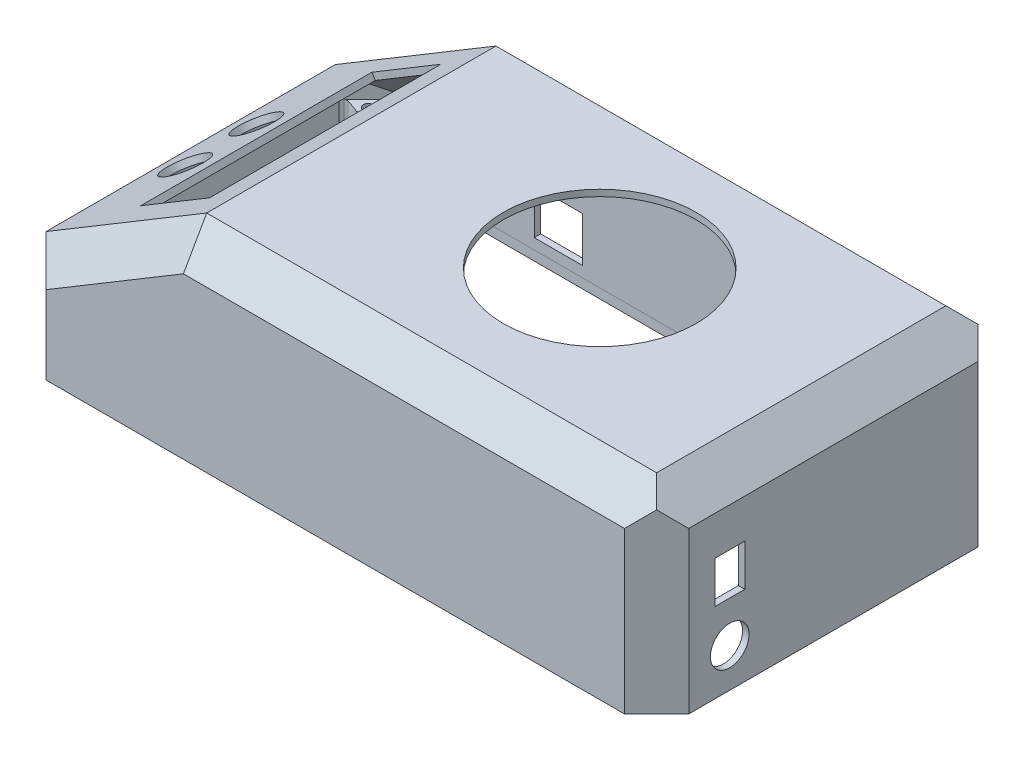
SolidWorks part; units mm, degrees
ref_plane "Front Plane" through (0, 0, 0) normal (0, 0, 1) x (1, 0, 0)
ref_plane "Top Plane" through (0, 0, 0) normal (0, 1, 0) x (1, 0, 0)
ref_plane "Right Plane" through (0, 0, 0) normal (1, 0, 0) x (0, 0, -1)
sketch "Sketch1" plane through (0, 0, 0) normal (0, 0, 1) x (1, 0, 0)
  line L0 (-200, 30) -> (-150, 60)
  line L1 (0, 60) -> (-150, 60)
  line L2 (0, 60) -> (0, 0)
  line L3 (0, 0) -> (-200, 0)
  line L4 (-200, 30) -> (-200, 0)
  dimension "D1" = 60
  dimension "D2" = 200
  dimension "D3" = 150
  dimension "D4" = 30
extrude "Boss-Extrude1" add sketch "Sketch1" along normal blind 110
chamfer "Chamfer1" distance 10 angle 45 8 edges at (0, 30, 110) (-75, 60, 110) (-200, 15, 110) (-175, 45, 110) (0, 30, 0) (-75, 60, 0) (-200, 15, 0) (-175, 45, 0)
sketch "Sketch2" plane through (-66.1765, 110.2941, 0) normal (-0.5145, 0.8575, 0) x (0.8575, 0.5145, 0)
  line L1 (-108.3969, -17.9949) -> (-133.3969, -17.9949)
  line L2 (-108.3969, -17.9949) -> (-108.3969, -89.9949)
  line L3 (-108.3969, -89.9949) -> (-133.3969, -89.9949)
  line L4 (-133.3969, -17.9949) -> (-133.3969, -89.9949)
  dimension "D1" = 25
  dimension "D2" = 72
chamfer "Chamfer2" distance 10 angle 45 1 edges at (0, 60, 55)
shell "Shell2" thickness 2
extrude "Cut-Extrude2" cut sketch "Sketch2" against normal blind 90
sketch "Sketch4" plane through (-66.1765, 110.2941, 0) normal (-0.5145, 0.8575, 0) x (0.8575, 0.5145, 0)
  circle A0 centre (-145.2108, -43.8631) radius 6.5
  circle A1 centre (-145.2841, -65.9395) radius 6.5
  dimension "D1" = 13
extrude "Cut-Extrude3" cut sketch "Sketch4" against normal blind 90 contours A1 | A0
sketch "Sketch5" plane through (0, 0, 0) normal (0, -1, 0) x (1, 0, 0)
  line L0 (-9.2474, 106.757) -> (-3.2561, 100.4838)
  line L1 (-10.8284, 2) -> (-2, 10.8284) construction
  line L2 (-10.0395, 2.6832) -> (-3.5134, 9.0462)
  line L3 (-189.1716, 108) -> (-198, 99.1716) construction
  line L4 (-190.1639, 107.0371) -> (-196.9025, 100.4015)
  line L5 (-189.1716, 2) -> (-198, 10.8284) construction
  line L6 (-190.4562, 3.2239) -> (-196.869, 9.6148)
  circle A0 centre (-8.5113, 101.4405) radius 1.5
  circle A1 centre (-8.5603, 8.5105) radius 1.5
  circle A2 centre (-191.5074, 101.4224) radius 1.5
  arc A3 (-3.2561, 100.4838) -> (-7.8703, 98.2418) centre (-2.196, 92.4329) ccw
  arc A4 (-11.6366, 101.7676) -> (-7.8703, 98.2418) centre (-7.1388, 102.7976) ccw
  arc A5 (-9.2474, 106.757) -> (-11.6366, 101.7676) centre (-36.6658, 116.8194) cw
  arc A6 (-11.3722, 8.1587) -> (-10.0395, 2.6832) centre (-17.6926, 3.7205) cw
  arc A7 (-7.4157, 11.2971) -> (-3.5134, 9.0462) centre (-1.767, 16.582) ccw
  arc A8 (-11.3722, 8.1587) -> (-7.4157, 11.2971) centre (-7.3108, 7.1018) cw
  circle A9 centre (-191.3565, 8.4217) radius 1.5
  arc A10 (-196.9025, 100.4015) -> (-192.2148, 98.8781) centre (-196.9968, 92.1377) cw
  arc A11 (-190.1639, 107.0371) -> (-188.808, 101.4281) centre (-184.4029, 105.4614) ccw
  arc A13 (-192.2148, 98.8781) -> (-188.808, 101.4281) centre (-192.9687, 103.436) ccw
  arc A14 (-196.869, 9.6148) -> (-192.0137, 11.3133) centre (-215.6683, 71.141) ccw
  arc A15 (-190.4562, 3.2239) -> (-188.778, 7.5123) centre (-185.6974, 3.8342) cw
  arc A16 (-192.0137, 11.3133) -> (-188.778, 7.5123) centre (-193.0727, 7.1341) cw
  point P12 (-6.4142, 6.4142)
  point P26 (-193.5858, 103.5858)
  point P38 (-193.5858, 6.4142)
  dimension "D1" = 3
  dimension "D3" = 3
  dimension "D5" = 3
  dimension "D7" = 3
  dimension "D2" = 3
  dimension "D4" = 3
  dimension "D6" = 3
  dimension "D8" = 3
extrude "Boss-Extrude2" add sketch "Sketch5" against normal blind 22 contours L6 A14 A16 A15 | A6 L2 A7 A8 | A1 | A9 | L4 A10 A13 A11 | A2 | L0 A3 A4 A5 | A0
fillet "Fillet2" radius 1 16 edges at (-196.7726, 11, 100.399) (-192.2148, 11, 98.8781) (-188.808, 11, 101.4281) (-190.1748, 11, 106.9968) (-196.8057, 11, 9.6341) (-190.4645, 11, 3.293) (-188.778, 11, 7.5123) (-192.0137, 11, 11.3133) (-9.3391, 11, 106.5107) (-3.3055, 11, 100.4771) (-7.8703, 11, 98.2418) (-11.6366, 11, 101.7676) (-7.4157, 11, 11.2971) (-11.3722, 11, 8.1587) (-10.0241, 11, 2.8044) (-3.729, 11, 9.0994)
sketch "Sketch6" plane through (0, 0, 0) normal (0, -1, 0) x (1, 0, 0)
  line L0 (-198.003, 10.8421) -> (-189.2119, 1.9947)
  line L1 (-189.1733, 108.0004) -> (-10.8729, 108.0004)
  line L2 (-198.003, 99.1844) -> (-198.003, 10.8421)
  line L3 (-189.2119, 1.9947) -> (-10.8281, 1.9947)
  line L4 (-2.0047, 99.2057) -> (-2.0047, 10.8285)
  line L5 (-198.003, 99.1844) -> (-189.1733, 108.0004)
  line L6 (-10.8729, 108.0004) -> (-2.0047, 99.2057)
  line L7 (-10.8281, 1.9947) -> (-2.0047, 10.8285)
extrude "Cut-Extrude4" cut sketch "Sketch6" against normal blind 3
sketch "Sketch7" plane through (0, 60, 0) normal (0, 1, 0) x (1, 0, 0)
  circle A0 centre (-74.0485, -53.6519) radius 30
  dimension "D1" = 60
extrude "Cut-Extrude5" cut sketch "Sketch7" against normal blind 61
sketch "Sketch9" plane through (0, 0, 0) normal (1, 0, 0) x (0, 0, -1)
  line L1 (-91.7701, 37.8789) -> (-82.5701, 37.8789)
  line L2 (-91.7701, 37.8789) -> (-91.7701, 24.8789)
  line L3 (-91.7701, 24.8789) -> (-82.5701, 24.8789)
  line L4 (-82.5701, 37.8789) -> (-82.5701, 24.8789)
  line L5 (-91.7701, 37.8789) -> (-82.5701, 24.8789) construction
  line L6 (-91.7701, 24.8789) -> (-82.5701, 37.8789) construction
  circle A0 centre (-87.2532, 12.0816) radius 6
  point P2 (-87.1701, 31.3789)
  dimension "D1" = 12
  dimension "D2" = 13
  dimension "D3" = 9.2
extrude "Cut-Extrude6" cut sketch "Sketch9" against normal blind 48 contours A0 | L2 L1 L4 L3
sketch "Sketch10" plane through (0, 0, 0) normal (0, 0, -1) x (-1, 0, 0)
  line L1 (131.0657, 20.3221) -> (146.0657, 20.3221)
  line L2 (131.0657, 20.3221) -> (131.0657, 6.3221)
  line L3 (131.0657, 6.3221) -> (146.0657, 6.3221)
  line L4 (146.0657, 20.3221) -> (146.0657, 6.3221)
  line L5 (131.0657, 20.3221) -> (146.0657, 6.3221) construction
  line L6 (131.0657, 6.3221) -> (146.0657, 20.3221) construction
  point P0 (138.5657, 13.3221)
  dimension "D1" = 14
  dimension "D2" = 15
extrude "Cut-Extrude7" cut sketch "Sketch10" against normal blind 48 contours L2 L1 L4 L3
